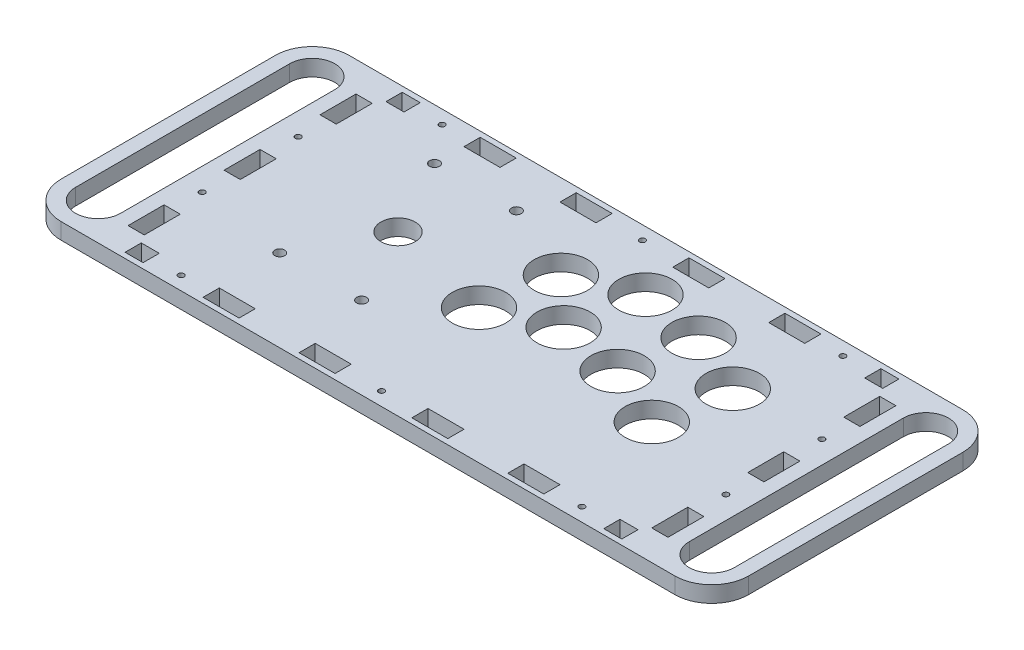
SolidWorks part; units mm, degrees
ref_plane "Front Plane" through (0, 0, 0) normal (0, 0, 1) x (1, 0, 0)
ref_plane "Top Plane" through (0, 0, 0) normal (0, 1, 0) x (1, 0, 0)
ref_plane "Right Plane" through (0, 0, 0) normal (1, 0, 0) x (0, 0, -1)
sketch "Sketch1" plane through (0, 0, 0) normal (0, 1, 0) x (1, 0, 0)
  line L1 (-150, -80) -> (150, -80)
  line L2 (-150, -80) -> (-150, 80)
  line L3 (-150, 80) -> (150, 80)
  line L4 (150, -80) -> (150, 80)
  line L5 (-150, -80) -> (150, 80) construction
  line L6 (-150, 80) -> (150, -80) construction
  point P0 (0, 0)
  dimension "D1" = 300
  dimension "D2" = 160
extrude "Boss-Extrude1" add sketch "Sketch1" along normal blind 9
sketch "Sketch2" plane through (0, 9, 0) normal (0, 1, 0) x (1, 0, 0)
  line L0 (-72, 8.675) -> (20, 8.675) construction
  line L1 (90, -12.325) -> (90, 8.675) construction
  line L2 (90, 8.675) -> (-72, 8.675) construction
  line L4 (-94.75, -34.325) -> (-49.25, -34.325) construction
  line L5 (-94.75, -34.325) -> (-94.75, 51.675) construction
  line L6 (-94.75, 51.675) -> (-49.25, 51.675) construction
  line L7 (-49.25, -34.325) -> (-49.25, 51.675) construction
  line L8 (-94.75, -34.325) -> (-49.25, 51.675) construction
  line L9 (-94.75, 51.675) -> (-49.25, -34.325) construction
  line L10 (27, 62) -> (150, 62) construction
  line L11 (150, -80) -> (150, 80) construction
  line L12 (150, 80) -> (-150, 80) construction
  circle A0 centre (-13, -5.325) radius 14.825
  circle A1 centre (20, 8.675) radius 14.825
  circle A2 centre (56, 2.675) radius 14.825
  circle A3 centre (90, -12.325) radius 14.825
  circle A4 centre (-72, 8.675) radius 9.5
  circle A5 centre (-94.75, 51.675) radius 2.75
  circle A6 centre (-49.25, 51.675) radius 2.75
  circle A7 centre (-94.75, -34.325) radius 2.75
  circle A8 centre (-49.25, -34.325) radius 2.75
  circle A9 centre (-6, 33.175) radius 14.825
  circle A10 centre (27, 47.175) radius 14.825
  circle A11 centre (62.5, 41.175) radius 14.825
  circle A12 centre (96.5, 26.175) radius 14.825
  dimension "D8" = 29.65
  dimension "D9" = 19
  dimension "D12" = 5.5
  dimension "D1" = 33
  dimension "D2" = 36
  dimension "D3" = 34
  dimension "D4" = 14
  dimension "D5" = 6
  dimension "D6" = 15
  dimension "D7" = 59
  dimension "D10" = 45.5
  dimension "D11" = 86
  dimension "D13" = 18
  dimension "D14" = 20
  dimension "D15" = 7
  dimension "D16" = 7
  dimension "D17" = 6.5
  dimension "D18" = 6.5
  dimension "D19" = 38.5
  dimension "D20" = 14
  dimension "D21" = 6
  dimension "D22" = 15
extrude "main buttons" cut sketch "Sketch2" against normal through all
sketch "Sketch4" plane through (0, 9, 0) normal (0, 1, 0) x (1, 0, 0)
  line L0 (-150, 80) -> (-150, -80) construction
  line L1 (-150, 63.3333) -> (-141, 63.3333)
  line L2 (-150, 63.3333) -> (-150, 43.3333)
  line L3 (-150, 43.3333) -> (-141, 43.3333)
  line L4 (-141, 63.3333) -> (-141, 43.3333)
  line L5 (-141, 80) -> (-141, 63.3333) construction
  line L6 (-150, 10) -> (-141, 10)
  line L7 (-150, 10) -> (-150, -10)
  line L8 (-150, -10) -> (-141, -10)
  line L9 (-141, 10) -> (-141, -10)
  line L10 (-150, -43.3333) -> (-141, -43.3333)
  line L11 (-150, -43.3333) -> (-150, -63.3333)
  line L12 (-150, -63.3333) -> (-141, -63.3333)
  line L13 (-141, -43.3333) -> (-141, -63.3333)
  line L14 (150, 80) -> (-150, 80) construction
  line L15 (-141, -43.3333) -> (-141, -26.6667) construction
  line L16 (-141, -26.6667) -> (-141, -10) construction
  line L17 (-141, -63.3333) -> (-141, -80) construction
  line L18 (-150, -80) -> (150, -80) construction
  line L19 (-141, 10) -> (-141, 26.6667) construction
  line L20 (-141, 26.6667) -> (-141, 43.3333) construction
  line L21 (-150, 26.6667) -> (-141, 26.6667) construction
  line L22 (-141, -26.6667) -> (-150, -26.6667) construction
  circle A0 centre (-145.5, -26.6667) radius 1.6
  circle A1 centre (-145.5, 26.6667) radius 1.6
  dimension "D3" = 3.2
  dimension "D1" = 9
  dimension "D2" = 20
  dimension "D4" = 33.3333
extrude "left mount" cut sketch "Sketch4" against normal through all
sketch "Sketch3" plane through (0, 9, 0) normal (0, 1, 0) x (1, 0, 0)
  line L0 (-150, -80) -> (150, -80) construction
  line L1 (-191, -80) -> (-150, -80) construction
  line L2 (-191, -80) -> (-191, 80) construction
  line L3 (-191, 80) -> (-150, 80) construction
  line L4 (-150, -80) -> (-150, 80)
  line L5 (-191, -80) -> (-150, 80) construction
  line L6 (-191, 80) -> (-150, -80) construction
  line L7 (-170.5, -59.5) -> (-170.5, 59.5) construction
  line L8 (-183, -59.5) -> (-183, 59.5)
  line L9 (-158, -59.5) -> (-158, 59.5)
  line L10 (-170.5, 72) -> (-150, 72) construction
  line L11 (-150, -80) -> (-170.5, -80)
  line L12 (-191, -59.5) -> (-191, 59.5)
  line L13 (-170.5, 80) -> (-150, 80)
  line L14 (-170.5, -72) -> (-150, -72) construction
  arc A0 (-183, -59.5) -> (-158, -59.5) centre (-170.5, -59.5) ccw
  arc A1 (-158, 59.5) -> (-183, 59.5) centre (-170.5, 59.5) ccw
  arc A2 (-191, 59.5) -> (-170.5, 80) centre (-170.5, 59.5) cw
  arc A3 (-191, -59.5) -> (-170.5, -80) centre (-170.5, -59.5) ccw
  point P0 (-170.5, 0)
  point P10 (-170.5, 0)
  dimension "D1" = 8
  dimension "D2" = 144
  dimension "D3" = 25
extrude "handle" add sketch "Sketch3" against normal up to surface (9 mm away) up to face at (-145.5, 0, -25.0667)
mirror "Mirror1" about plane through (0, 0, 0) normal (1, 0, 0) of "handle", "left mount"
sketch "Sketch6" plane through (0, 9, 0) normal (0, 1, 0) x (1, 0, 0)
  line L1 (138, 77) -> (128, 77)
  line L2 (138, 77) -> (138, 68)
  line L3 (138, 68) -> (128, 68)
  line L4 (128, 77) -> (128, 68)
  line L5 (94.6667, 77) -> (74.6667, 77)
  line L6 (94.6667, 77) -> (94.6667, 68)
  line L7 (94.6667, 68) -> (74.6667, 68)
  line L8 (74.6667, 77) -> (74.6667, 68)
  line L9 (170.5, 80) -> (-170.5, 80) construction
  line L11 (141, 43.3333) -> (141, 63.3333) construction
  dimension "D2" = 20
  dimension "D1" = 33.3333
  dimension "D3" = 10
  dimension "D4" = 9
  dimension "D5" = 3
  dimension "D6" = 3
extrude "Cut-Extrude1" cut sketch "Sketch6" against normal through all
mirror "Mirror3" about plane through (0, 0, 0) normal (1, 0, 0) of "Cut-Extrude1"
sketch "Sketch7" plane through (0, 9, 0) normal (0, 1, 0) x (1, 0, 0)
  line L0 (74.6667, 77) -> (74.6667, 68) construction
  line L1 (21.3333, 77) -> (41.3333, 77)
  line L2 (21.3333, 77) -> (21.3333, 68)
  line L3 (21.3333, 68) -> (41.3333, 68)
  line L4 (41.3333, 77) -> (41.3333, 68)
  line L5 (94.6667, 77) -> (74.6667, 77) construction
  line L6 (74.6667, 68) -> (94.6667, 68) construction
  line L7 (94.6667, 68) -> (94.6667, 77) construction
  line L8 (74.6667, 77) -> (74.6667, 68) construction
  line L9 (94.6667, 77) -> (74.6667, 77) construction
  line L10 (74.6667, 68) -> (94.6667, 68) construction
  line L11 (94.6667, 68) -> (94.6667, 77) construction
  line L12 (128, 77) -> (128, 68) construction
  line L13 (128, 77) -> (128, 68) construction
  line L14 (41.3333, 77) -> (74.6667, 77) construction
  line L15 (74.6667, 77) -> (94.6667, 77) construction
  line L16 (94.6667, 77) -> (128, 77) construction
  line L17 (0, 0) -> (0, 80) construction
  line L18 (170.5, 80) -> (-170.5, 80) construction
  line L19 (-41.3333, 77) -> (-41.3333, 68)
  line L20 (-21.3333, 77) -> (-41.3333, 77)
  line L21 (-21.3333, 77) -> (-21.3333, 68)
  line L22 (-21.3333, 68) -> (-41.3333, 68)
extrude "Cut-Extrude2" cut sketch "Sketch7" against normal through all
sketch "Sketch8" plane through (0, 9, 0) normal (0, 1, 0) x (1, 0, 0)
  line L0 (-128, 72.5) -> (-94.6667, 72.5) construction
  line L1 (-128, 77) -> (-128, 68) construction
  line L2 (-94.6667, 68) -> (-94.6667, 77) construction
  line L3 (-94.6667, 72.5) -> (-21.3333, 72.5) construction
  line L4 (-21.3333, 68) -> (-21.3333, 77) construction
  line L5 (-21.3333, 72.5) -> (21.3333, 72.5) construction
  line L6 (21.3333, 77) -> (21.3333, 68) construction
  line L7 (21.3333, 72.5) -> (94.6667, 72.5) construction
  line L8 (94.6667, 68) -> (94.6667, 77) construction
  line L9 (94.6667, 72.5) -> (128, 72.5) construction
  line L10 (128, 77) -> (128, 68) construction
  circle A0 centre (-111.3333, 72.5) radius 1.6
  circle A1 centre (0, 72.5) radius 1.6
  circle A2 centre (111.3333, 72.5) radius 1.6
  circle A3 centre (-145.5, 26.6667) radius 1.6 construction
extrude "M3 clearance holes" cut sketch "Sketch8" against normal through all
mirror "Mirror4" about plane through (0, 0, 0) normal (0, 0, 1) of "Cut-Extrude1", "Mirror3", "Cut-Extrude2", "M3 clearance holes"
sketch "Sketch5" plane through (0, 9, 0) normal (0, 1, 0) x (1, 0, 0)
  line L0 (-97.5, 51.675) -> (-97.5, -34.325) construction
  line L1 (0, 80) -> (0, -80) construction
  line L2 (170.5, 80) -> (-170.5, 80) construction
  line L3 (-170.5, -80) -> (170.5, -80) construction
  line L4 (-119.25, 33.3333) -> (119.25, 33.3333) construction
  line L5 (-141, 53.3333) -> (-97.5, 53.3333) construction
  line L6 (-141, 43.3333) -> (-141, 63.3333) construction
  line L7 (-119.25, 53.3333) -> (-119.25, 33.3333) construction
  circle A0 centre (-94.75, 51.675) radius 2.75 construction
  circle A1 centre (-94.75, -34.325) radius 2.75 construction
  circle A2 centre (-119.25, 33.3333) radius 14.825
  circle A3 centre (119.25, 33.3333) radius 14.825
  circle A4 centre (-13, -5.325) radius 14.825 construction
  circle A5 centre (-94.75, 51.675) radius 2.75
  circle A6 centre (-94.75, -34.325) radius 2.75
  point P15 (0, 33.3333)
  dimension "D1" = 20
extrude "LR button layout 1" [suppressed] cut sketch "Sketch5" against normal through all
equation "\"nuthole\"=3.2"
equation "\"D3@Sketch4\"=\"nuthole\""
equation "\"connectorspacing\"= \"D4@Sketch4\""
equation "\"D1@Sketch6\"=\"connectorspacing\""
equation "\"connector_thickness\"=9"
equation "\"D1@Sketch4\"=\"connector_thickness\""
equation "\"connector_length\"=20"
equation "\"D2@Sketch4\"=\"connector_length\""
equation "\"D3@Sketch6\"=\"connector_length\"/2"
equation "\"D4@Sketch6\"=\"connector_thickness\""
equation "\"margin\"=3"
equation "\"D5@Sketch6\"=\"margin\""
equation "\"D6@Sketch6\"=\"margin\""
